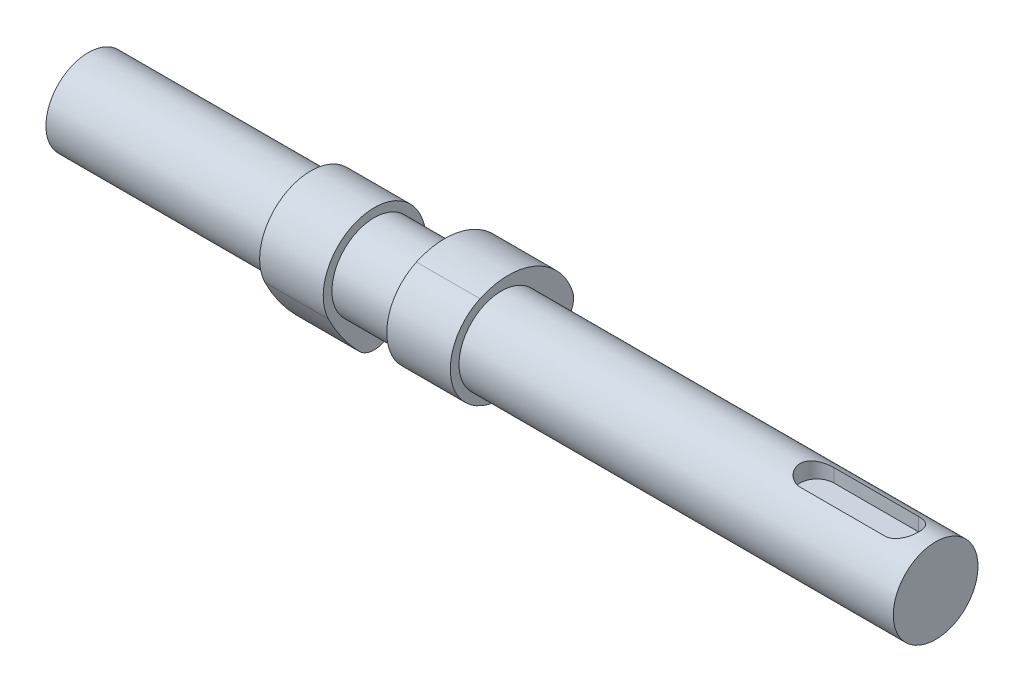
SolidWorks part; units mm, degrees
ref_plane "Front Plane" through (0, 0, 0) normal (0, 0, 1) x (1, 0, 0)
ref_plane "Top Plane" through (0, 0, 0) normal (0, 1, 0) x (1, 0, 0)
ref_plane "Right Plane" through (0, 0, 0) normal (1, 0, 0) x (0, 0, -1)
sketch "Sketch1" plane through (0, 0, 0) normal (1, 0, 0) x (0, 0, -1)
  circle A0 centre (0, 0) radius 10
extrude "Boss-Extrude1" add sketch "Sketch1" against normal blind 75 and the other way blind 125
sketch "Sketch2" plane through (0, 0, 0) normal (1, 0, 0) x (0, 0, -1)
  line L0 (0, 0) -> (10, 0) construction
  arc A0 (-5.0466, 10.945) -> (5.3434, -10.8032) centre (0, 0) ccw
  circle A1 centre (0, 0) radius 10 construction
  arc A2 (15.5442, -3.5787) -> (16.7794, 1.6295) centre (12.0524, 0) ccw
  arc A3 (-5.0466, 10.945) -> (16.7794, 1.6295) centre (1.6529, -3.5849) cw
  arc A4 (5.3434, -10.8032) -> (15.5442, -3.5787) centre (-12.3905, 25.0508) ccw
  dimension "D1" = 10
  dimension "D2" = 16
  dimension "D3" = 40
  dimension "D4" = 12.5
extrude "Boss-Extrude2" add sketch "Sketch2" along normal mid plane 15 from offset 15 separate body
mirror "Mirror1" about plane through (0, 0, 0) normal (1, 0, 0) of bodies 102
move or copy body "Body-Move/Copy1" bodies to move or copy 103 copy no rotation origin (0, 0, 0) rotation axis (-1, 0, 0) rotation angle 90
ref_plane "Plane1" through (0, 10, 0) normal (0, 1, 0) x (1, 0, 0)
sketch "Sketch3" plane through (0, 10, 0) normal (0, 1, 0) x (1, 0, 0)
  line L0 (125, 0) -> (74.0831, 0) construction
  line L1 (125, -10) -> (125, 10) construction
  line L2 (117, 0) -> (97, 0) construction
  line L3 (117, -4) -> (97, -4)
  line L4 (117, 4) -> (97, 4)
  arc A0 (117, -4) -> (117, 4) centre (117, 0) ccw
  arc A1 (97, 4) -> (97, -4) centre (97, 0) ccw
  point P7 (107, 0)
  dimension "D3" = 4
  dimension "D1" = 20
  dimension "D2" = 8
extrude "Cut-Extrude1" cut sketch "Sketch3" against normal blind 4
